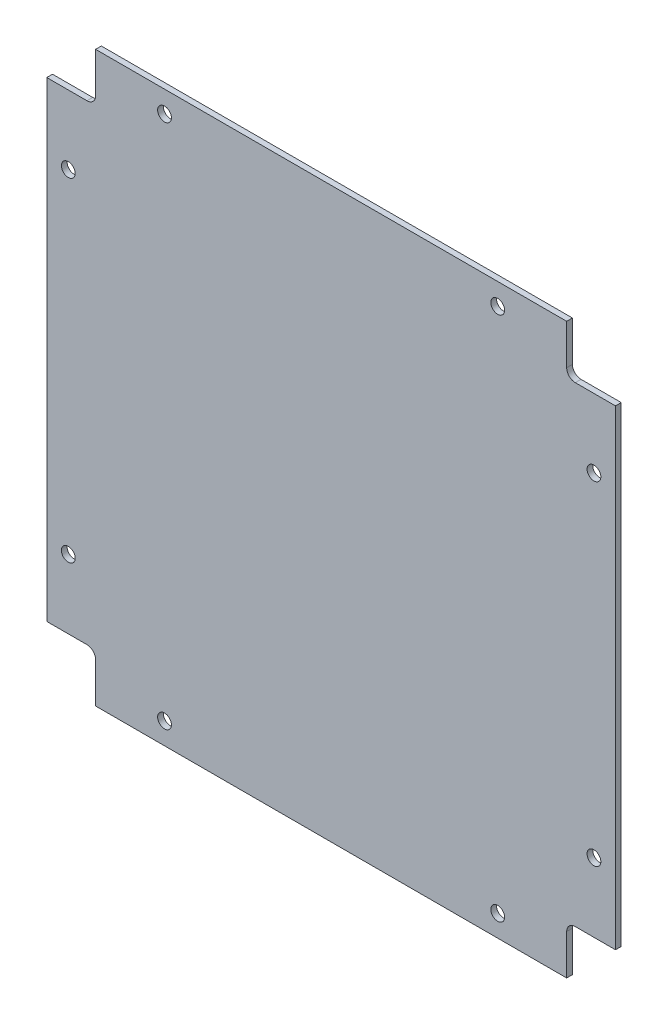
SolidWorks part; units mm, degrees
material "1100-H12 Rod (SS)"
ref_plane "Frontal" through (0, 0, 0) normal (0, 0, 1) x (1, 0, 0)
ref_plane "Superior" through (0, 0, 0) normal (0, 1, 0) x (1, 0, 0)
ref_plane "Direito" through (0, 0, 0) normal (1, 0, 0) x (0, 0, -1)
sketch "Sketch1" plane through (0, 0, 0) normal (0, 0, 1) x (1, 0, 0)
  line L1 (-49.5, -49.5) -> (49.5, -49.5)
  line L2 (-49.5, -49.5) -> (-49.5, 49.5)
  line L3 (-49.5, 49.5) -> (49.5, 49.5)
  line L4 (49.5, -49.5) -> (49.5, 49.5)
  line L5 (-49.5, -49.5) -> (49.5, 49.5) construction
  line L6 (-49.5, 49.5) -> (49.5, -49.5) construction
  point P0 (0, 0)
  dimension "D1" = 99
  dimension "D2" = 99
extrude "Boss-Extrude1" add sketch "Sketch1" along normal mid plane 1
sketch "Sketch2" plane through (0, 0, 0.5) normal (0, 0, 1) x (1, 0, 0)
  line L0 (-49.5, 49.5) -> (-49.5, -49.5) construction
  line L1 (-49.5, 49.5) -> (-41, 49.5)
  line L2 (-49.5, 49.5) -> (-49.5, 41)
  line L3 (-49.5, 41) -> (-42.5, 41)
  line L4 (-41, 49.5) -> (-41, 42.5)
  line L5 (49.5, 49.5) -> (41, 49.5)
  line L6 (49.5, 49.5) -> (49.5, 41)
  line L7 (49.5, 41) -> (42.5, 41)
  line L8 (41, 49.5) -> (41, 42.5)
  line L9 (-49.5, -49.5) -> (-41, -49.5)
  line L10 (-49.5, -49.5) -> (-49.5, -41)
  line L11 (-49.5, -41) -> (-42.5, -41)
  line L12 (-41, -49.5) -> (-41, -42.5)
  line L13 (49.5, -49.5) -> (41, -49.5)
  line L14 (49.5, -49.5) -> (49.5, -41)
  line L15 (49.5, -41) -> (42.5, -41)
  line L16 (41, -49.5) -> (41, -42.5)
  arc A0 (-41, 42.5) -> (-42.5, 41) centre (-42.5, 42.5) cw
  arc A1 (41, 42.5) -> (42.5, 41) centre (42.5, 42.5) ccw
  arc A2 (42.5, -41) -> (41, -42.5) centre (42.5, -42.5) ccw
  arc A3 (-42.5, -41) -> (-41, -42.5) centre (-42.5, -42.5) cw
  dimension "D1" = 1.5
  dimension "D3" = 1.5
  dimension "D5" = 1.5
  dimension "D7" = 1.5
  dimension "D2" = 8.5
  dimension "D4" = 8.5
  dimension "D6" = 8.5
  dimension "D8" = 8.5
  dimension "D9" = 8.5
  dimension "D10" = 8.5
  dimension "D11" = 8.5
  dimension "D12" = 8.5
extrude "Cut-Extrude1" cut sketch "Sketch2" against normal through all
hole_wizard "M2 Hole1 - B" positions "Sketch4" profile "Sketch3" hole size "M2" standard "DIN"
sketch "Sketch4" plane through (0, 0, 0.5) normal (0, 0, 1) x (1, 0, 0)
  line L0 (-41, 42.5) -> (-41, 49.5) construction
  line L1 (41, 49.5) -> (-41, 49.5) construction
  line L2 (41, 49.5) -> (41, 42.5) construction
  line L3 (-49.5, 41) -> (-49.5, -41) construction
  line L4 (-49.5, 41) -> (-42.5, 41) construction
  line L5 (-42.5, -41) -> (-49.5, -41) construction
  line L6 (49.5, -41) -> (49.5, 41) construction
  line L7 (-41, -49.5) -> (41, -49.5) construction
  point P0 (-45.75, 29)
  point P2 (-29, 45.75)
  point P4 (29, 45.75)
  point P6 (45.75, 29)
  point P8 (45.75, -29)
  point P10 (29, -45.75)
  point P12 (-29, -45.75)
  point P14 (-45.75, -29)
  dimension "D1" = 12
  dimension "D2" = 3.75
  dimension "D3" = 12
  dimension "D4" = 3.75
  dimension "D5" = 12
  dimension "D6" = 12
  dimension "D7" = 3.75
  dimension "D8" = 3.75
sketch "Sketch3" plane through (-45.75, 29, 0.5) normal (1, 0, 0) x (0, -1, 0)
  line L0 (0, 0) -> (0, 3.721)
  line L1 (0, 3.721) -> (1.2, 3)
  line L2 (1.2, 3) -> (1.2, 0)
  line L5 (1.2, 0) -> (0, 0)
  line L10 (0, 3.721) -> (-1.2, 3) construction
  line L11 (0, -6.35) -> (0, 107.95) construction
  dimension "Hole Dia." = 2.4
  dimension "Hole Depth" = 3
  dimension "Drill Angle" = 118
fillet "Fillet1" [suppressed] radius 0.5
